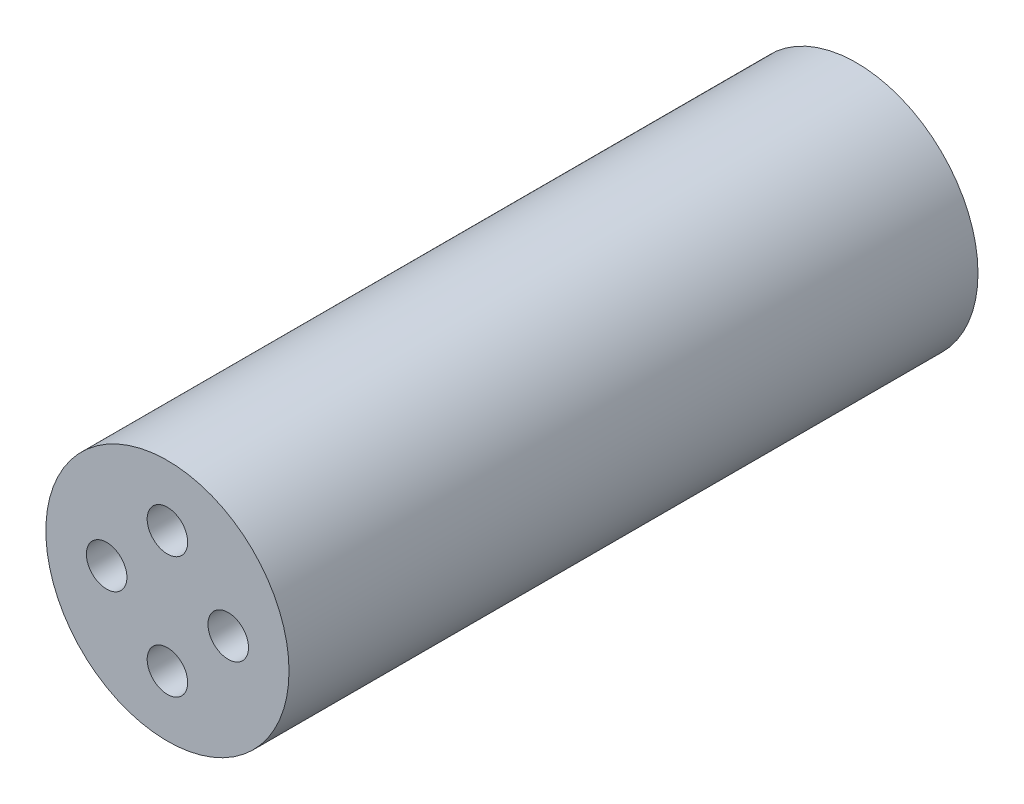
SolidWorks part; units mm, degrees
ref_plane "Front Plane" through (0, 0, 0) normal (0, 0, 1) x (1, 0, 0)
ref_plane "Top Plane" through (0, 0, 0) normal (0, 1, 0) x (1, 0, 0)
ref_plane "Right Plane" through (0, 0, 0) normal (1, 0, 0) x (0, 0, -1)
sketch "Sketch1" plane through (0, 0, 0) normal (0, 0, 1) x (1, 0, 0)
  circle A0 centre (0, 0) radius 15
  dimension "D1" = 30
extrude "Boss-Extrude1" add sketch "Sketch1" along normal blind 85
sketch "Sketch2" plane through (0, 0, 85) normal (0, 0, 1) x (1, 0, 0)
  line L0 (0, 0) -> (0, 15) construction
  circle A0 centre (0, 0) radius 15 construction
  circle A1 centre (0, 7.5) radius 2.5
  circle A2 centre (7.5, 0) radius 2.5
  circle A3 centre (0, -7.5) radius 2.5
  circle A4 centre (-7.5, 0) radius 2.5
  point P16 (0, 0)
  dimension "D1" = 5
  dimension "D2" = 4
extrude "Cut-Extrude1" cut sketch "Sketch2" against normal blind 20
